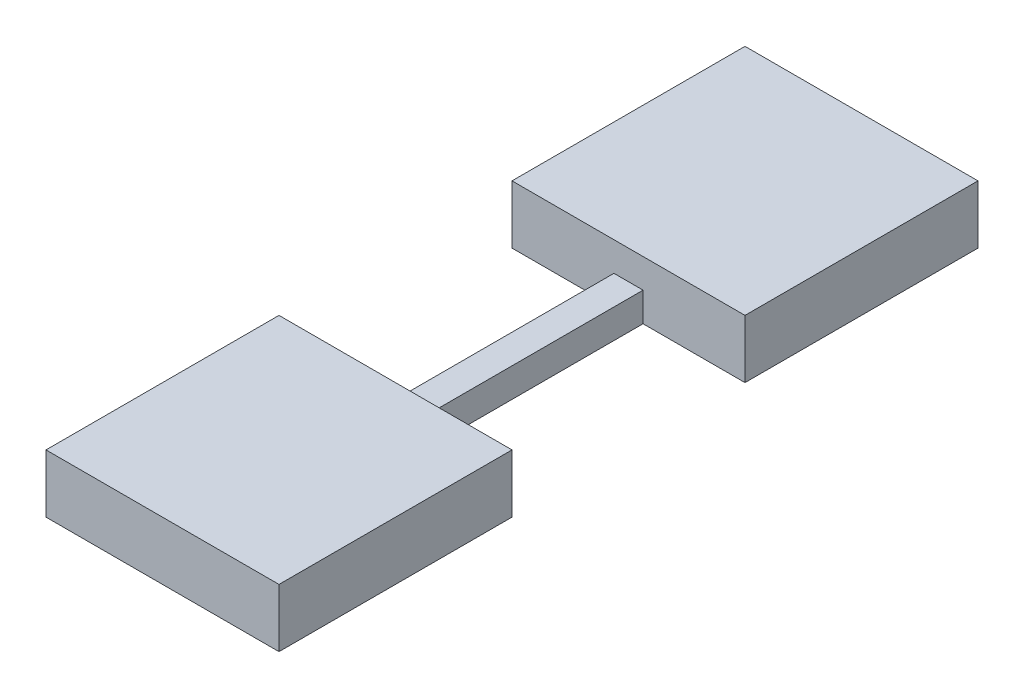
SolidWorks part; units mm, degrees
ref_plane "Front Plane" through (0, 0, 0) normal (0, 0, 1) x (1, 0, 0)
ref_plane "Top Plane" through (0, 0, 0) normal (0, 1, 0) x (1, 0, 0)
ref_plane "Right Plane" through (0, 0, 0) normal (1, 0, 0) x (0, 0, -1)
sketch "Sketch3" plane through (0, 0, 0) normal (0, 1, 0) x (1, 0, 0)
  line L0 (-2.0314, 2.7749) -> (-2.0314, -1.2251)
  line L1 (-2.0314, -1.2251) -> (1.9686, -1.2251)
  line L2 (1.9686, -1.2251) -> (1.9686, 2.7749)
  line L3 (-2.0314, 2.7749) -> (-0.2814, 2.7749)
  line L4 (-0.2814, 2.7749) -> (-0.2814, 6.7749)
  line L5 (1.9686, 2.7749) -> (0.2186, 2.7749)
  line L6 (0.2186, 2.7749) -> (0.2186, 6.7749)
  line L7 (-0.2814, 6.7749) -> (-2.0314, 6.7749)
  line L8 (-2.0314, 6.7749) -> (-2.0314, 10.7749)
  line L9 (-2.0314, 10.7749) -> (1.9686, 10.7749)
  line L10 (1.9686, 10.7749) -> (1.9686, 6.7749)
  line L11 (1.9686, 6.7749) -> (0.2186, 6.7749)
  dimension "D1" = 4
  dimension "D2" = 1.75
  dimension "D3" = 1.75
  dimension "D4" = 4
  dimension "D5" = 4
  dimension "D6" = 4
  dimension "D7" = 4
extrude "Boss-Extrude1" add sketch "Sketch3" along normal blind 1
sketch "Sketch4" plane through (0, 1, 0) normal (0, 1, 0) x (1, 0, 0)
  line L0 (-0.2814, 2.7749) -> (0.2186, 2.7749)
  line L1 (0.2186, 2.7749) -> (0.2186, 6.7749)
  line L2 (0.2186, 6.7749) -> (-0.2814, 6.7749)
  line L3 (-0.2814, 6.7749) -> (-0.2814, 2.7749)
extrude "Cut-Extrude1" cut sketch "Sketch4" against normal blind 0.5
